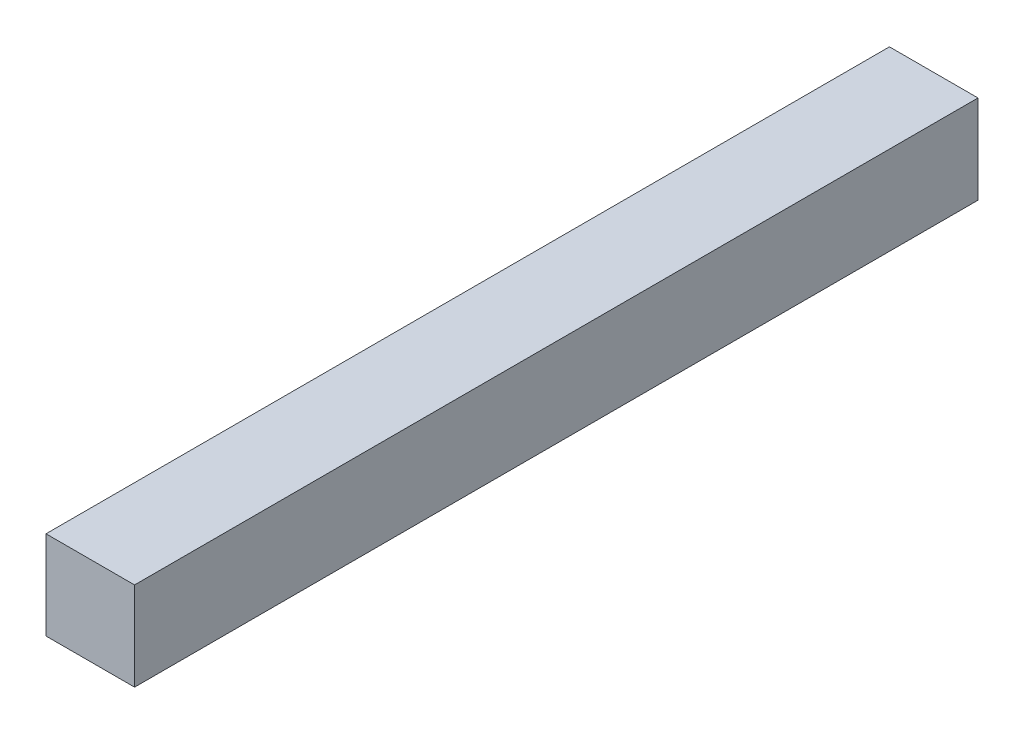
SolidWorks part; units mm, degrees
ref_plane "Front Plane" through (0, 0, 0) normal (0, 0, 1) x (1, 0, 0)
ref_plane "Top Plane" through (0, 0, 0) normal (0, 1, 0) x (1, 0, 0)
ref_plane "Right Plane" through (0, 0, 0) normal (1, 0, 0) x (0, 0, -1)
sketch "Sketch1" plane through (0, 0, 0) normal (0, 0, 1) x (1, 0, 0)
  line L1 (-10.5, 10.5) -> (10.5, 10.5)
  line L2 (-10.5, 10.5) -> (-10.5, -10.5)
  line L3 (-10.5, -10.5) -> (10.5, -10.5)
  line L4 (10.5, 10.5) -> (10.5, -10.5)
  line L5 (-10.5, 10.5) -> (10.5, -10.5) construction
  line L6 (-10.5, -10.5) -> (10.5, 10.5) construction
  point P0 (0, 0)
extrude "Boss-Extrude1" add sketch "Sketch1" along normal blind 200
